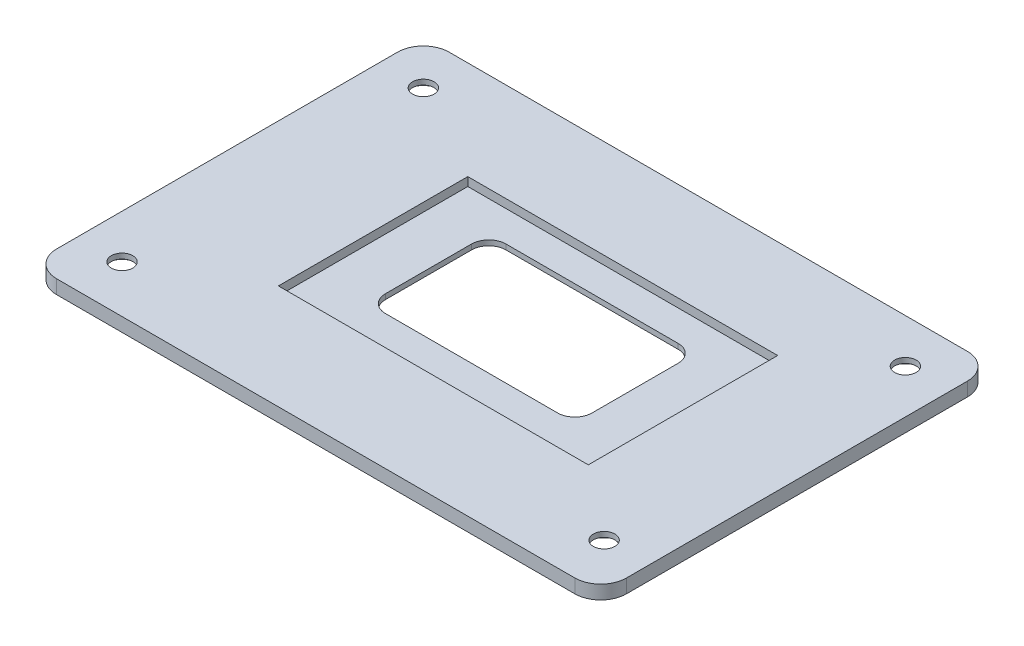
SolidWorks part; units mm, degrees
ref_plane "前视基准面" through (0, 0, 0) normal (0, 0, 1) x (1, 0, 0)
ref_plane "上视基准面" through (0, 0, 0) normal (0, 1, 0) x (1, 0, 0)
ref_plane "右视基准面" through (0, 0, 0) normal (1, 0, 0) x (0, 0, -1)
sketch "草图1" plane through (0, 0, 0) normal (0, 1, 0) x (1, 0, 0)
  line L1 (-30.1, -22.8) -> (30.1, -22.8)
  line L2 (-33.1, -19.8) -> (-33.1, 19.8)
  line L3 (-30.1, 22.8) -> (30.1, 22.8)
  line L4 (33.1, -19.8) -> (33.1, 19.8)
  line L5 (-33.1, -22.8) -> (33.1, 22.8) construction
  line L6 (-33.1, 22.8) -> (33.1, -22.8) construction
  arc A0 (30.1, 22.8) -> (33.1, 19.8) centre (30.1, 19.8) cw
  arc A1 (-33.1, 19.8) -> (-30.1, 22.8) centre (-30.1, 19.8) cw
  arc A2 (30.1, -22.8) -> (33.1, -19.8) centre (30.1, -19.8) ccw
  arc A3 (-30.1, -22.8) -> (-33.1, -19.8) centre (-30.1, -19.8) cw
  point P0 (0, 0)
  dimension "D3" = 3
  dimension "D4" = 3
  dimension "D1" = 45.6
  dimension "D2" = 66.2
extrude "凸台-拉伸1" add sketch "草图1" along normal blind 1.6
sketch "草图3" plane through (0, 1.6, 0) normal (0, 1, 0) x (1, 0, 0)
  line L0 (-30.1, -22.8) -> (30.1, -22.8) construction
  line L1 (-8.5, -6.2) -> (11.5, -6.2)
  line L2 (-10.5, -4.2) -> (-10.5, 5.8)
  line L3 (-8.5, 7.8) -> (11.5, 7.8)
  line L4 (13.5, -4.2) -> (13.5, 5.8)
  line L5 (-10.5, -6.2) -> (13.5, 7.8) construction
  line L6 (-10.5, 7.8) -> (13.5, -6.2) construction
  line L8 (33.1, -19.8) -> (33.1, 19.8) construction
  arc A0 (11.5, -6.2) -> (13.5, -4.2) centre (11.5, -4.2) ccw
  arc A1 (-8.5, -6.2) -> (-10.5, -4.2) centre (-8.5, -4.2) cw
  arc A2 (11.5, 7.8) -> (13.5, 5.8) centre (11.5, 5.8) cw
  arc A3 (-10.5, 5.8) -> (-8.5, 7.8) centre (-8.5, 5.8) cw
  point P0 (0, 0)
  dimension "D3" = 2
  dimension "D1" = 24
  dimension "D2" = 14
  dimension "D4" = 19.6
  dimension "D5" = 16.6
extrude "磁带窗" cut sketch "草图3" against normal up to next
sketch "草图5" plane through (0, 0, 0) normal (0, -1, 0) x (1, 0, 0)
  line L0 (-33.1, -19.8) -> (-33.1, 19.8) construction
  line L1 (30.1, -22.8) -> (-30.1, -22.8) construction
  circle A0 centre (-28, -17.7) radius 2.6
  circle A1 centre (28, -17.7) radius 2.6
  circle A2 centre (28, 17.3) radius 2.6
  circle A3 centre (-28, 17.3) radius 2.6
  point P0 (-28, -17.7)
  point P10 (28, -17.7)
  point P13 (28, 17.3)
  point P16 (-28, 17.3)
  dimension "D3" = 5.2
  dimension "D1" = 5.1
  dimension "D2" = 5.1
  dimension "D4" = 2
  dimension "D5" = 2
extrude "正螺丝孔" cut sketch "草图5" against normal blind 1
sketch "草图7" plane through (0, 1, 0) normal (0, -1, 0) x (1, 0, 0)
  circle A0 centre (-28, -17.7) radius 1.25
  circle A1 centre (28, -17.7) radius 1.25
  circle A2 centre (28, 17.3) radius 1.25
  circle A3 centre (-28, 17.3) radius 1.25
  dimension "D1" = 2.5
  dimension "D2" = 2
  dimension "D3" = 2
extrude "背螺丝孔" cut sketch "草图7" against normal up to next
sketch "草图9" plane through (0, 1.6, 0) normal (0, 1, 0) x (1, 0, 0)
  line L1 (-16.4991, -10.6372) -> (19.5009, -10.6372)
  line L2 (-16.4991, -10.6372) -> (-16.4991, 11.3628)
  line L3 (-16.4991, 11.3628) -> (19.5009, 11.3628)
  line L4 (19.5009, -10.6372) -> (19.5009, 11.3628)
  line L5 (-16.4991, -10.6372) -> (19.5009, 11.3628) construction
  line L6 (-16.4991, 11.3628) -> (19.5009, -10.6372) construction
  point P0 (1.5009, 0.3628)
  dimension "D1" = 36
  dimension "D2" = 22
extrude "屏幕槽" cut sketch "草图9" against normal blind 1 contours L2 L1 L4 L3
